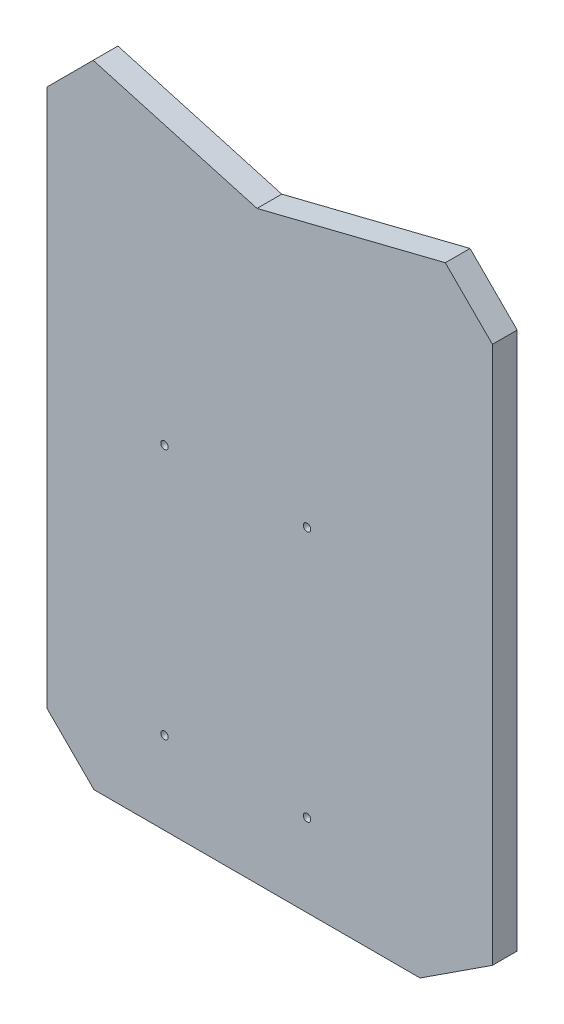
SolidWorks part; units mm, degrees
ref_plane "前视基准面" through (0, 0, 0) normal (0, 0, 1) x (1, 0, 0)
ref_plane "上视基准面" through (0, 0, 0) normal (0, 1, 0) x (1, 0, 0)
ref_plane "右视基准面" through (0, 0, 0) normal (1, 0, 0) x (0, 0, -1)
sketch "草图3" plane through (0, 0, 0) normal (0, 0, 1) x (1, 0, 0)
  line L0 (-276.0634, 169.4497) -> (-276.0634, -47.8767)
  line L1 (-115.0318, 188.4918) -> (-191.1216, 169.4497)
  line L2 (-257.3289, 188.1842) -> (-191.1216, 169.4497)
  line L3 (-276.0634, -47.8767) -> (-257.0213, -66.9188)
  line L5 (-115.0318, 188.4918) -> (-101.5072, 174.9672)
  line L7 (-101.5072, 174.9672) -> (-95.9897, 169.4497)
  line L8 (-257.3289, 188.1842) -> (-276.0634, 169.4497)
  line L12 (-95.9897, 169.4497) -> (-95.9897, -47.8767)
  line L13 (-95.9897, -47.8767) -> (-125.2219, -66.9188)
  line L14 (-125.2219, -66.9188) -> (-257.0213, -66.9188)
extrude "凸台-拉伸2" add sketch "草图3" along normal blind 10
sketch "草图5" plane through (0, 0, 0) normal (0, 0, -1) x (-1, 0, 0)
  line L1 (164.0657, 77.6136) -> (233.6558, 77.6136)
  line L2 (164.0657, 77.6136) -> (164.0657, -40.4614)
  line L3 (164.0657, -40.4614) -> (233.6558, -40.4614)
  line L4 (233.6558, 77.6136) -> (233.6558, -40.4614)
hole_wizard "大小mm 暗销孔1" positions "草图6" profile "草图7" hole size "Ø3.0" standard "BSI" end condition through all
sketch "草图6" plane through (0, 0, 0) normal (0, 0, -1) x (-1, 0, 0)
  point P0 (170.9107, 67.9166)
  point P2 (228.5221, 67.9166)
  point P4 (228.5221, -33.6165)
  point P6 (170.9107, -33.6165)
sketch "草图7" plane through (-170.9107, 67.9166, 0) normal (1, 0, 0) x (0, 1, 0)
  line L0 (0, 0) -> (0, 10)
  line L1 (0, 10) -> (1.5, 10)
  line L2 (1.5, 10) -> (1.5, 0)
  line L5 (1.5, 0) -> (0, 0)
  line L11 (0, -6.35) -> (0, 107.95) construction
  dimension "通孔孔直径" = 3
  dimension "通孔孔深度" = 10
